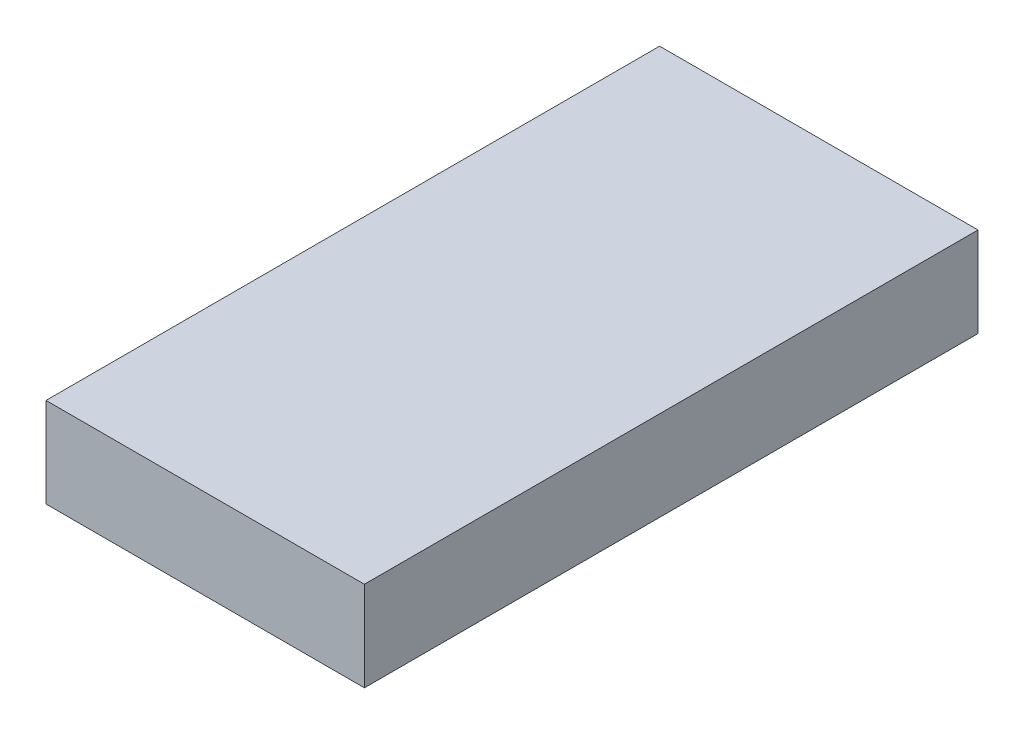
SolidWorks part; units mm, degrees
ref_plane "前视基准面" through (0, 0, 0) normal (0, 0, 1) x (1, 0, 0)
ref_plane "上视基准面" through (0, 0, 0) normal (0, 1, 0) x (1, 0, 0)
ref_plane "右视基准面" through (0, 0, 0) normal (1, 0, 0) x (0, 0, -1)
other "Configuration Table"
sketch "草图1" plane through (0, 0, 0) normal (0, 1, 0) x (1, 0, 0)
  line L1 (-22, -42.4) -> (22, -42.4)
  line L2 (-22, -42.4) -> (-22, 42.4)
  line L3 (-22, 42.4) -> (22, 42.4)
  line L4 (22, -42.4) -> (22, 42.4)
  line L5 (-22, -42.4) -> (22, 42.4) construction
  line L6 (-22, 42.4) -> (22, -42.4) construction
  point P0 (0, 0)
  dimension "D1" = 44
  dimension "D2" = 84.8
extrude "凸台-拉伸1" add sketch "草图1" along normal blind 12.4
